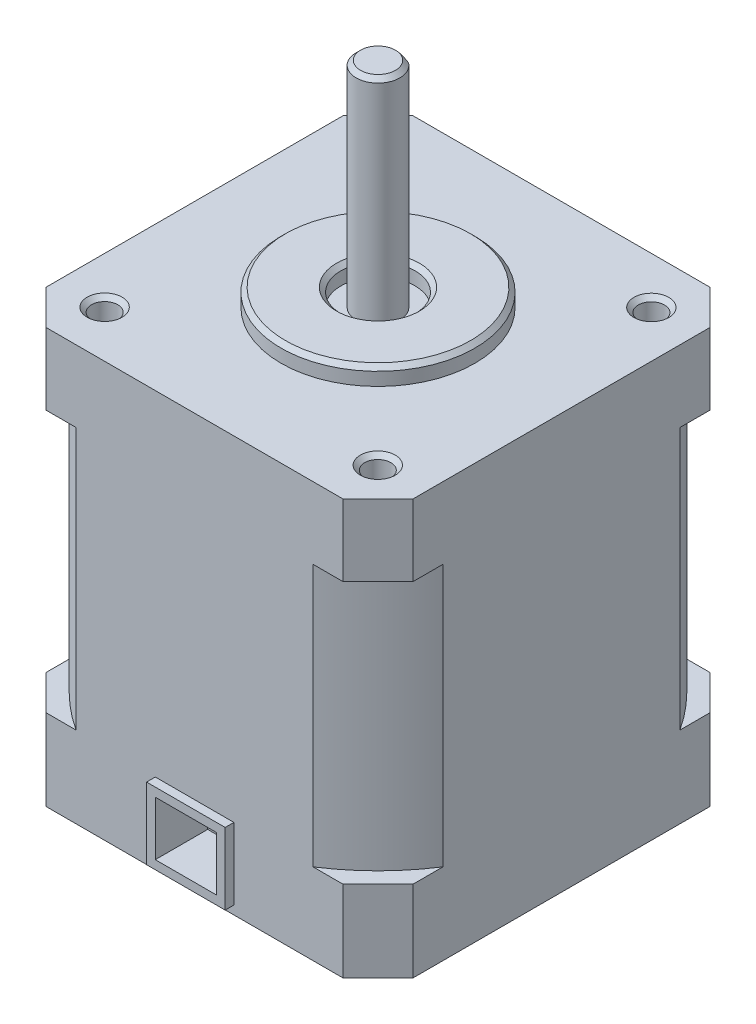
SolidWorks part; units mm, degrees
ref_plane "Front Plane" through (0, 0, 0) normal (0, 0, 1) x (1, 0, 0)
ref_plane "Top Plane" through (0, 0, 0) normal (0, 1, 0) x (1, 0, 0)
ref_plane "Right Plane" through (0, 0, 0) normal (1, 0, 0) x (0, 0, -1)
sketch "Sketch1" plane through (0, 0, 0) normal (0, 1, 0) x (1, 0, 0)
  line L1 (-21, 21) -> (21, 21)
  line L2 (-21, 21) -> (-21, -21)
  line L3 (-21, -21) -> (21, -21)
  line L4 (21, 21) -> (21, -21)
  line L5 (-21, 21) -> (21, -21) construction
  line L6 (-21, -21) -> (21, 21) construction
  point P0 (0, 0)
extrude "Boss-Extrude1" add sketch "Sketch1" along normal blind 47.5
chamfer "Chamfer1" distance 4 angle 45 4 edges at (-21, 23.75, -21) (21, 23.75, -21) (21, 23.75, 21) (-21, 23.75, 21)
sketch "Sketch2" plane through (0, 47.5, 0) normal (0, -1, 0) x (1, 0, 0)
  circle A0 centre (0, 0) radius 11.1
  circle A1 centre (0, 0) radius 4.25
extrude "Boss-Extrude2" add sketch "Sketch2" against normal blind 2
sketch "Sketch4" plane through (0, 47.5, 0) normal (0, 1, 0) x (1, 0, 0)
  circle A0 centre (0, 0) radius 2.5
extrude "Boss-Extrude3" add sketch "Sketch4" along normal blind 24.5
chamfer "Chamfer2" distance 0.5 angle 45 1 edges at (0, 72, 2.5)
sketch "Sketch5" plane through (0, 72, 0) normal (0, 1, 0) x (1, 0, 0)
  line L0 (0, -2.5) -> (0, 2) construction
  line L1 (-1.8672, 2) -> (1.9736, 2)
  line L2 (1.9736, 2) -> (0.0532, 2.9964)
  line L3 (0.0532, 2.9964) -> (-1.8672, 2)
  circle A0 centre (0, 0) radius 2.5 construction
  circle A1 centre (0, 0) radius 2 construction
extrude "Cut-Extrude1" cut sketch "Sketch5" against normal blind 18
sketch "Sketch6" plane through (0, 47.5, 0) normal (0, 1, 0) x (1, 0, 0)
  line L0 (0, -21.5) -> (0, 21.5) construction
  line L1 (-21.5, 21.5) -> (21.5, -21.5) construction
  line L2 (-21.5, -21.5) -> (21.5, 21.5) construction
  circle A0 centre (-15.6378, 15.6621) radius 1.5
  circle A1 centre (15.6621, 15.6378) radius 1.5
  circle A2 centre (15.6378, -15.6621) radius 1.5
  circle A3 centre (-15.6621, -15.6378) radius 1.5
  point P2 (0, 0)
extrude "Cut-Extrude2" cut sketch "Sketch6" against normal blind 5
sketch "Sketch7" plane through (0, 0, 0) normal (0, 1, 0) x (1, 0, 0)
  line L0 (-21, 17) -> (-21, -17) construction
  circle A0 centre (0, 0) radius 25
  circle A1 centre (0, 0) radius 36.8523
extrude "Cut-Extrude3" cut sketch "Sketch7" along normal blind 30 from offset 9.3
sketch "Sketch8" plane through (0, 0, 21) normal (0, 0, 1) x (1, 0, 0)
  line L0 (0, 8.8632) -> (0, 1.3) construction
  line L2 (-4.5, 9.1802) -> (4.5, 9.1802)
  line L3 (-4.5, 9.1802) -> (-4.5, 0.983)
  line L4 (-4.5, 0.983) -> (4.5, 0.983)
  line L5 (4.5, 9.1802) -> (4.5, 0.983)
  line L6 (-4.5, 9.1802) -> (4.5, 0.983) construction
  line L7 (-4.5, 0.983) -> (4.5, 9.1802) construction
  point P3 (0, 5.0816)
extrude "Extrude-Thin1" add sketch "Sketch8" along normal blind 1 thin
sketch "Sketch9" plane through (0, 0, 21) normal (0, 0, 1) x (1, 0, 0)
  line L4 (-3.5, 1.983) -> (3.5, 1.983)
  line L5 (3.5, 1.983) -> (3.5, 8.1802)
  line L6 (3.5, 8.1802) -> (-3.5, 8.1802)
  line L7 (-3.5, 8.1802) -> (-3.5, 1.983)
  line L8 (-3.5, 1.983) -> (3.5, 1.983)
  line L9 (3.5, 1.983) -> (3.5, 8.1802)
  line L10 (3.5, 8.1802) -> (-3.5, 8.1802)
  line L11 (-3.5, 8.1802) -> (-3.5, 1.983)
  dimension "D1" = 0
extrude "Cut-Extrude4" cut sketch "Sketch9" against normal blind 5
chamfer "Chamfer3" distance 0.5 angle 45 6 edges at (0, 49.5, -11.1) (0, 49.5, -4.25) (-15.6621, 47.5, 17.1378) (15.6378, 47.5, 17.1621) (-15.6378, 47.5, -14.1621) (15.6621, 47.5, -14.1378)
